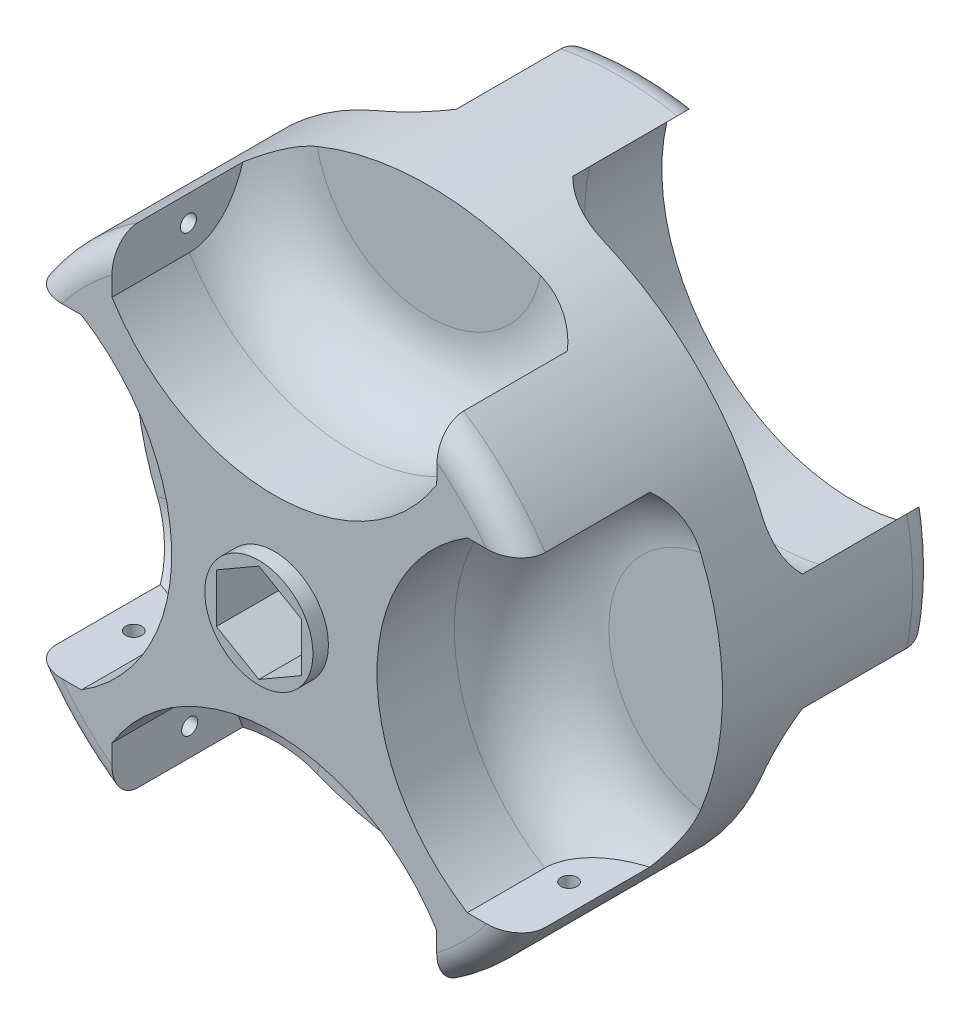
SolidWorks part; units mm, degrees
ref_plane "Alzado" through (0, 0, 0) normal (0, 0, 1) x (1, 0, 0)
ref_plane "Planta" through (0, 0, 0) normal (0, 1, 0) x (1, 0, 0)
ref_plane "Vista lateral" through (0, 0, 0) normal (1, 0, 0) x (0, 0, -1)
sketch "Croquis1" plane through (0, 0, 0) normal (0, 0, 1) x (1, 0, 0)
  circle A0 centre (0, 0) radius 19
extrude "Saliente-Extruir1" add sketch "Croquis1" along normal blind 24
sketch "Croquis6" plane through (0, 0, 0) normal (0, 0, 1) x (1, 0, 0)
  circle A0 centre (0, 0) radius 3.5
extrude "Saliente-Extruir3" add sketch "Croquis6" along normal blind 25
sketch "Croquis9" plane through (0, 0, 0) normal (0, 0, 1) x (1, 0, 0)
  line L1 (0, 3.1754) -> (-2.75, 1.5877)
  line L2 (-2.75, 1.5877) -> (-2.75, -1.5877)
  line L3 (-2.75, -1.5877) -> (0, -3.1754)
  line L4 (0, -3.1754) -> (2.75, -1.5877)
  line L5 (2.75, -1.5877) -> (2.75, 1.5877)
  line L6 (2.75, 1.5877) -> (0, 3.1754)
  circle A0 centre (0, 0) radius 2.75 construction
extrude "Cortar-Extruir5" cut sketch "Croquis9" along normal blind 28
sketch "Croquis13" plane through (0, 0, 0) normal (0, 0, 1) x (1, 0, 0)
  line L15 (-3.7631, 18.6236) -> (-1.3958, 16.2563)
  line L16 (3.7631, 18.6236) -> (1.3958, 16.2563)
  line L17 (18.6236, 3.7631) -> (16.2563, 1.3958)
  line L18 (18.6236, -3.7631) -> (16.2563, -1.3958)
  line L19 (1.3958, -16.2563) -> (3.7631, -18.6236)
  line L20 (-1.3784, -16.1809) -> (-3.7631, -18.6236)
  line L21 (-18.6236, -3.7631) -> (-16.2563, -1.3958)
  line L22 (-18.6236, 3.7631) -> (-16.2563, 1.3958)
  circle A0 centre (0, 0) radius 19 construction
  arc A1 (-1.3958, 16.2563) -> (-16.2563, 1.3958) centre (-13.435, 13.435) cw
  arc A2 (-16.2563, -1.3958) -> (-1.3784, -16.1809) centre (-13.435, -13.435) cw
  arc A3 (1.3958, -16.2563) -> (16.2563, -1.3958) centre (13.435, -13.435) cw
  arc A4 (1.3958, 16.2563) -> (16.2563, 1.3958) centre (13.435, 13.435) ccw
  arc A5 (-3.7631, 18.6236) -> (-18.6236, 3.7631) centre (0, 0) ccw
  arc A6 (-18.6236, -3.7631) -> (-3.7631, -18.6236) centre (0, 0) ccw
  arc A7 (3.7631, -18.6236) -> (18.6236, -3.7631) centre (0, 0) ccw
  arc A8 (18.6236, 3.7631) -> (3.7631, 18.6236) centre (0, 0) ccw
extrude "Cortar-Extruir10" cut sketch "Croquis13" against normal blind 1 and the other way blind 10
sketch "Croquis18" plane through (0, 0, 24) normal (0, 0, 1) x (1, 0, 0)
  line L0 (-10.5039, 15.8325) -> (-10.5039, 12.4854)
  line L1 (-15.8325, 10.5039) -> (-12.4854, 10.5039)
  line L2 (-15.8325, -10.5039) -> (-12.4854, -10.5039)
  line L3 (-10.5039, -15.8325) -> (-10.5039, -12.4854)
  line L4 (10.5039, -15.8325) -> (10.5039, -12.4854)
  line L5 (12.4854, -10.5039) -> (15.8325, -10.5039)
  line L6 (12.4854, 10.5039) -> (15.8325, 10.5039)
  line L7 (10.5039, 12.4854) -> (10.557, 15.7972)
  arc A0 (-12.4854, 10.5039) -> (-12.4854, -10.5039) centre (-19, 0) cw
  arc A2 (-10.5039, -12.4854) -> (10.5039, -12.4854) centre (0, -19) cw
  arc A4 (12.4854, -10.5039) -> (12.4854, 10.5039) centre (19, 0) cw
  arc A6 (-10.5039, 12.4854) -> (10.5039, 12.4854) centre (0, 19) ccw
  arc A9 (-15.8325, 10.5039) -> (-15.8325, -10.5039) centre (0, 0) ccw
  arc A10 (10.557, 15.7972) -> (-10.5039, 15.8325) centre (0, 0) ccw
  arc A11 (15.8325, -10.5039) -> (15.8325, 10.5039) centre (0, 0) ccw
  arc A12 (-10.5039, -15.8325) -> (10.5039, -15.8325) centre (0, 0) ccw
extrude "Cortar-Extruir11" cut sketch "Croquis18" against normal blind 10
fillet "Redondeo1" radius 1.7 4 edges at (-13.435, -13.435, 24) (13.435, -13.435, 24) (13.4575, 13.4125, 24) (-13.435, 13.435, 24)
fillet "Redondeo2" radius 1.7 4 edges at (-19, 0, 0) (0, 19, 0) (19, 0, 0) (0, -19, 0)
fillet "Redondeo3" radius 5 4 edges at (-6.6399, 0, 14) (0, -6.6399, 14) (6.6399, 0, 14) (0, 6.6399, 14)
fillet "Redondeo4" radius 5 4 edges at (-4.6914, 4.6914, 10) (-4.7188, -4.6641, 10) (4.6914, -4.6914, 10) (4.6914, 4.6914, 10)
hole_wizard "Taladro de margen para #0003" positions "Croquis26" profile "Croquis25" hole size "#000" standard "Ansi Inch"
sketch "Croquis26" plane through (10.3012, -0.165, 0) normal (-0.9999, 0.016, 0) x (0, 0, 1)
  point P0 (18.9257, 14.3226)
sketch "Croquis25" plane through (10.5307, 14.1557, 18.9257) normal (0, 0, 1) x (-0.016, -0.9999, 0)
  line L0 (0, 0) -> (0, 1.3129)
  line L1 (0, 1.3129) -> (0.5207, 1)
  line L2 (0.5207, 1) -> (0.5207, 0)
  line L5 (0.5207, 0) -> (0, 0)
  line L10 (0, 1.3129) -> (-0.5207, 1) construction
  line L11 (0, -6.35) -> (0, 107.95) construction
  dimension "Diámetro de taladro" = 1.0414
  dimension "Profundidad de taladro" = 1
  dimension "Ángulo de perforador" = 118
hole_wizard "Taladro de margen para #0004" positions "Croquis29" profile "Croquis28" hole size "#000" standard "Ansi Inch"
sketch "Croquis29" plane through (-10.5039, 0, 0) normal (1, 0, 0) x (0, 0, -1)
  point P1 (-19.0584, 14.1694)
sketch "Croquis28" plane through (-10.5039, 14.1694, 19.0584) normal (0, 1, 0) x (0, 0, -1)
  line L0 (0, 0) -> (0, 1.3129)
  line L1 (0, 1.3129) -> (0.5207, 1)
  line L2 (0.5207, 1) -> (0.5207, 0)
  line L5 (0.5207, 0) -> (0, 0)
  line L10 (0, 1.3129) -> (-0.5207, 1) construction
  line L11 (0, -6.35) -> (0, 107.95) construction
  dimension "Diámetro de taladro" = 1.0414
  dimension "Profundidad de taladro" = 1
  dimension "Ángulo de perforador" = 118
hole_wizard "Taladro de margen para #0005" positions "Croquis32" profile "Croquis31" hole size "#000" standard "Ansi Inch"
sketch "Croquis32" plane through (0, 10.5039, 0) normal (0, -1, 0) x (-1, 0, 0)
  point P0 (-14.1013, -18.9203)
sketch "Croquis31" plane through (14.1013, 10.5039, 18.9203) normal (1, 0, 0) x (0, 0, -1)
  line L0 (0, 0) -> (0, 1.3129)
  line L1 (0, 1.3129) -> (0.5207, 1)
  line L2 (0.5207, 1) -> (0.5207, 0)
  line L5 (0.5207, 0) -> (0, 0)
  line L10 (0, 1.3129) -> (-0.5207, 1) construction
  line L11 (0, -6.35) -> (0, 107.95) construction
  dimension "Diámetro de taladro" = 1.0414
  dimension "Profundidad de taladro" = 1
  dimension "Ángulo de perforador" = 118
hole_wizard "Taladro de margen para #0006" positions "Croquis35" profile "Croquis34" hole size "#000" standard "Ansi Inch"
sketch "Croquis35" plane through (0, -10.5039, 0) normal (0, 1, 0) x (1, 0, 0)
  point P0 (14.0469, -18.9817)
sketch "Croquis34" plane through (14.0469, -10.5039, 18.9817) normal (1, 0, 0) x (0, 0, 1)
  line L0 (0, 0) -> (0, 1.3129)
  line L1 (0, 1.3129) -> (0.5207, 1)
  line L2 (0.5207, 1) -> (0.5207, 0)
  line L5 (0.5207, 0) -> (0, 0)
  line L10 (0, 1.3129) -> (-0.5207, 1) construction
  line L11 (0, -6.35) -> (0, 107.95) construction
  dimension "Diámetro de taladro" = 1.0414
  dimension "Profundidad de taladro" = 1
  dimension "Ángulo de perforador" = 118
hole_wizard "Taladro de margen para #0007" positions "Croquis38" profile "Croquis37" hole size "#000" standard "Ansi Inch"
sketch "Croquis38" plane through (10.5039, 0, 0) normal (-1, 0, 0) x (0, 0, 1)
  point P0 (19.0489, -14.0806)
sketch "Croquis37" plane through (10.5039, -14.0806, 19.0489) normal (0, 1, 0) x (0, 0, 1)
  line L0 (0, 0) -> (0, 1.3129)
  line L1 (0, 1.3129) -> (0.5207, 1)
  line L2 (0.5207, 1) -> (0.5207, 0)
  line L5 (0.5207, 0) -> (0, 0)
  line L10 (0, 1.3129) -> (-0.5207, 1) construction
  line L11 (0, -6.35) -> (0, 107.95) construction
  dimension "Diámetro de taladro" = 1.0414
  dimension "Profundidad de taladro" = 1
  dimension "Ángulo de perforador" = 118
hole_wizard "Taladro de margen para #0008" positions "Croquis41" profile "Croquis40" hole size "#000" standard "Ansi Inch"
sketch "Croquis41" plane through (-10.5039, 0, 0) normal (1, 0, 0) x (0, 0, -1)
  point P0 (-18.9737, -14.0617)
sketch "Croquis40" plane through (-10.5039, -14.0617, 18.9737) normal (0, 1, 0) x (0, 0, -1)
  line L0 (0, 0) -> (0, 1.3129)
  line L1 (0, 1.3129) -> (0.5207, 1)
  line L2 (0.5207, 1) -> (0.5207, 0)
  line L5 (0.5207, 0) -> (0, 0)
  line L10 (0, 1.3129) -> (-0.5207, 1) construction
  line L11 (0, -6.35) -> (0, 107.95) construction
  dimension "Diámetro de taladro" = 1.0414
  dimension "Profundidad de taladro" = 1
  dimension "Ángulo de perforador" = 118
hole_wizard "Taladro de margen para #0009" positions "Croquis44" profile "Croquis43" hole size "#000" standard "Ansi Inch"
sketch "Croquis44" plane through (0, -10.5039, 0) normal (0, 1, 0) x (1, 0, 0)
  point P0 (-14.1011, -18.9978)
sketch "Croquis43" plane through (-14.1011, -10.5039, 18.9978) normal (1, 0, 0) x (0, 0, 1)
  line L0 (0, 0) -> (0, 1.3129)
  line L1 (0, 1.3129) -> (0.5207, 1)
  line L2 (0.5207, 1) -> (0.5207, 0)
  line L5 (0.5207, 0) -> (0, 0)
  line L10 (0, 1.3129) -> (-0.5207, 1) construction
  line L11 (0, -6.35) -> (0, 107.95) construction
  dimension "Diámetro de taladro" = 1.0414
  dimension "Profundidad de taladro" = 1
  dimension "Ángulo de perforador" = 118
hole_wizard "Taladro de margen para #00010" positions "Croquis47" profile "Croquis46" hole size "#000" standard "Ansi Inch"
sketch "Croquis47" plane through (0, 10.5039, 0) normal (0, -1, 0) x (-1, 0, 0)
  point P0 (14.1304, -18.9958)
sketch "Croquis46" plane through (-14.1304, 10.5039, 18.9958) normal (1, 0, 0) x (0, 0, -1)
  line L0 (0, 0) -> (0, 1.3129)
  line L1 (0, 1.3129) -> (0.5207, 1)
  line L2 (0.5207, 1) -> (0.5207, 0)
  line L5 (0.5207, 0) -> (0, 0)
  line L10 (0, 1.3129) -> (-0.5207, 1) construction
  line L11 (0, -6.35) -> (0, 107.95) construction
  dimension "Diámetro de taladro" = 1.0414
  dimension "Profundidad de taladro" = 1
  dimension "Ángulo de perforador" = 118
hole_wizard "Taladro de margen para #00011" positions "Croquis50" profile "Croquis49" hole size "#000" standard "Ansi Inch"
sketch "Croquis50" plane through (7.3824, -7.2071, 0) normal (-0.7156, 0.6986, 0) x (0, 0, 1)
  point P0 (5.0029, -14.1968)
sketch "Croquis49" plane through (-2.535, -17.3656, 5.0029) normal (0, 0, 1) x (-0.6986, -0.7156, 0)
  line L0 (0, 0) -> (0, 1.3129)
  line L1 (0, 1.3129) -> (0.5207, 1)
  line L2 (0.5207, 1) -> (0.5207, 0)
  line L5 (0.5207, 0) -> (0, 0)
  line L10 (0, 1.3129) -> (-0.5207, 1) construction
  line L11 (0, -6.35) -> (0, 107.95) construction
  dimension "Diámetro de taladro" = 1.0414
  dimension "Profundidad de taladro" = 1
  dimension "Ángulo de perforador" = 118
hole_wizard "Taladro de margen para #00012" positions "Croquis53" profile "Croquis52" hole size "#000" standard "Ansi Inch"
sketch "Croquis53" plane through (7.4302, 7.4302, 0) normal (-0.7071, -0.7071, 0) x (-0.7071, 0.7071, 0)
  point P0 (-14.1345, -5.0033)
sketch "Croquis52" plane through (17.4248, -2.5643, 5.0033) normal (0, 0, 1) x (0.7071, -0.7071, 0)
  line L0 (0, 0) -> (0, 1.3129)
  line L1 (0, 1.3129) -> (0.5207, 1)
  line L2 (0.5207, 1) -> (0.5207, 0)
  line L5 (0.5207, 0) -> (0, 0)
  line L10 (0, 1.3129) -> (-0.5207, 1) construction
  line L11 (0, -6.35) -> (0, 107.95) construction
  dimension "Diámetro de taladro" = 1.0414
  dimension "Profundidad de taladro" = 1
  dimension "Ángulo de perforador" = 118
hole_wizard "Taladro de margen para #00013" positions "Croquis56" profile "Croquis55" hole size "#000" standard "Ansi Inch"
sketch "Croquis56" plane through (-7.4302, -7.4302, 0) normal (0.7071, 0.7071, 0) x (0, 0, -1)
  point P0 (-5.1015, -14.1617)
sketch "Croquis55" plane through (2.5836, -17.4441, 5.1015) normal (0, 0, 1) x (-0.7071, 0.7071, 0)
  line L0 (0, 0) -> (0, 1.3129)
  line L1 (0, 1.3129) -> (0.5207, 1)
  line L2 (0.5207, 1) -> (0.5207, 0)
  line L5 (0.5207, 0) -> (0, 0)
  line L10 (0, 1.3129) -> (-0.5207, 1) construction
  line L11 (0, -6.35) -> (0, 107.95) construction
  dimension "Diámetro de taladro" = 1.0414
  dimension "Profundidad de taladro" = 1
  dimension "Ángulo de perforador" = 118
hole_wizard "Taladro de margen para #00014" positions "Croquis59" profile "Croquis58" hole size "#000" standard "Ansi Inch"
sketch "Croquis59" plane through (-7.4302, 7.4302, 0) normal (0.7071, -0.7071, 0) x (-0.7071, -0.7071, 0)
  point P0 (14.1575, -5.0415)
sketch "Croquis58" plane through (-17.4411, -2.5806, 5.0415) normal (0, 0, 1) x (0.7071, 0.7071, 0)
  line L0 (0, 0) -> (0, 1.3129)
  line L1 (0, 1.3129) -> (0.5207, 1)
  line L2 (0.5207, 1) -> (0.5207, 0)
  line L5 (0.5207, 0) -> (0, 0)
  line L10 (0, 1.3129) -> (-0.5207, 1) construction
  line L11 (0, -6.35) -> (0, 107.95) construction
  dimension "Diámetro de taladro" = 1.0414
  dimension "Profundidad de taladro" = 1
  dimension "Ángulo de perforador" = 118
hole_wizard "Taladro de margen para #00015" positions "Croquis62" profile "Croquis61" hole size "#000" standard "Ansi Inch"
sketch "Croquis62" plane through (-7.4302, -7.4302, 0) normal (0.7071, 0.7071, 0) x (0.7071, -0.7071, 0)
  point P0 (-14.1053, -5.0224)
sketch "Croquis61" plane through (-17.4042, 2.5437, 5.0224) normal (0, 0, 1) x (-0.7071, 0.7071, 0)
  line L0 (0, 0) -> (0, 1.3129)
  line L1 (0, 1.3129) -> (0.5207, 1)
  line L2 (0.5207, 1) -> (0.5207, 0)
  line L5 (0.5207, 0) -> (0, 0)
  line L10 (0, 1.3129) -> (-0.5207, 1) construction
  line L11 (0, -6.35) -> (0, 107.95) construction
  dimension "Diámetro de taladro" = 1.0414
  dimension "Profundidad de taladro" = 1
  dimension "Ángulo de perforador" = 118
hole_wizard "Taladro de margen para #00016" positions "Croquis65" profile "Croquis64" hole size "#000" standard "Ansi Inch"
sketch "Croquis65" plane through (7.4302, 7.4302, 0) normal (-0.7071, -0.7071, 0) x (0, 0, 1)
  point P0 (5.0427, 14.1315)
sketch "Croquis64" plane through (-2.5622, 17.4227, 5.0427) normal (0, 0, 1) x (0.7071, -0.7071, 0)
  line L0 (0, 0) -> (0, 1.3129)
  line L1 (0, 1.3129) -> (0.5207, 1)
  line L2 (0.5207, 1) -> (0.5207, 0)
  line L5 (0.5207, 0) -> (0, 0)
  line L10 (0, 1.3129) -> (-0.5207, 1) construction
  line L11 (0, -6.35) -> (0, 107.95) construction
  dimension "Diámetro de taladro" = 1.0414
  dimension "Profundidad de taladro" = 1
  dimension "Ángulo de perforador" = 118
hole_wizard "Taladro de margen para #00017" positions "Croquis68" profile "Croquis67" hole size "#000" standard "Ansi Inch"
sketch "Croquis68" plane through (-7.4302, 7.4302, 0) normal (0.7071, -0.7071, 0) x (-0.7071, -0.7071, 0)
  point P0 (-14.145, -5.0106)
sketch "Croquis67" plane through (2.5718, 17.4323, 5.0106) normal (0, 0, 1) x (0.7071, 0.7071, 0)
  line L0 (0, 0) -> (0, 1.3129)
  line L1 (0, 1.3129) -> (0.5207, 1)
  line L2 (0.5207, 1) -> (0.5207, 0)
  line L5 (0.5207, 0) -> (0, 0)
  line L10 (0, 1.3129) -> (-0.5207, 1) construction
  line L11 (0, -6.35) -> (0, 107.95) construction
  dimension "Diámetro de taladro" = 1.0414
  dimension "Profundidad de taladro" = 1
  dimension "Ángulo de perforador" = 118
hole_wizard "Taladro de margen para #00018" positions "Croquis71" profile "Croquis70" hole size "#000" standard "Ansi Inch"
sketch "Croquis71" plane through (7.4302, -7.4302, 0) normal (-0.7071, 0.7071, 0) x (0.7071, 0.7071, 0)
  point P0 (14.0884, -4.9856)
sketch "Croquis70" plane through (17.3923, 2.5318, 4.9856) normal (0, 0, 1) x (-0.7071, -0.7071, 0)
  line L0 (0, 0) -> (0, 1.3129)
  line L1 (0, 1.3129) -> (0.5207, 1)
  line L2 (0.5207, 1) -> (0.5207, 0)
  line L5 (0.5207, 0) -> (0, 0)
  line L10 (0, 1.3129) -> (-0.5207, 1) construction
  line L11 (0, -6.35) -> (0, 107.95) construction
  dimension "Diámetro de taladro" = 1.0414
  dimension "Profundidad de taladro" = 1
  dimension "Ángulo de perforador" = 118
